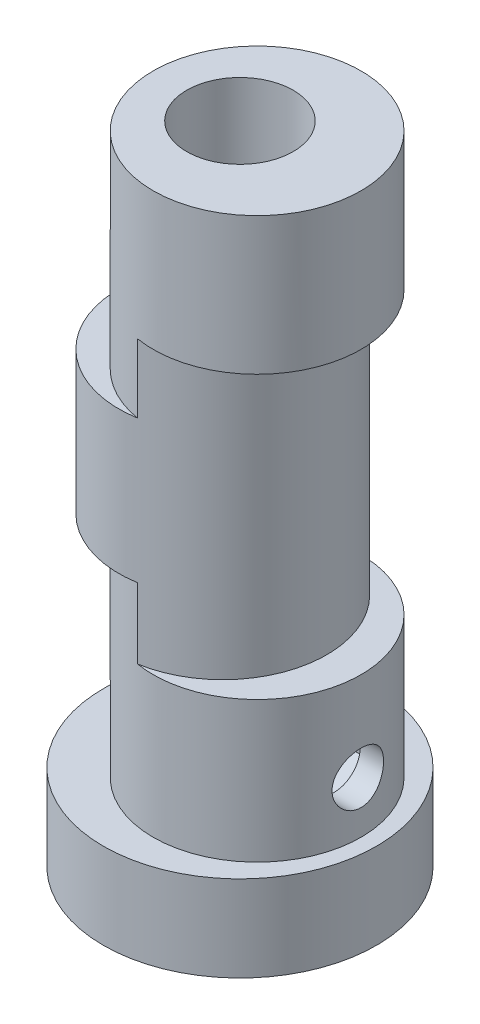
SolidWorks part; units mm, degrees
ref_plane "Front Plane" through (0, 0, 0) normal (0, 0, 1) x (1, 0, 0)
ref_plane "Top Plane" through (0, 0, 0) normal (0, 1, 0) x (1, 0, 0)
ref_plane "Right Plane" through (0, 0, 0) normal (1, 0, 0) x (0, 0, -1)
sketch "Sketch1" plane through (0, 0, 0) normal (0, 1, 0) x (1, 0, 0)
  circle A0 centre (0, 0) radius 7.95
  dimension "D1" = 15.9
extrude "Boss-Extrude1" add sketch "Sketch1" along normal blind 5
sketch "Sketch2" plane through (0, 5, 0) normal (0, 1, 0) x (1, 0, 0)
  line L0 (0, 0) -> (1, 0) construction
  circle A0 centre (1, 0) radius 6.05
  dimension "D2" = 12.1
  dimension "D1" = 1
extrude "Boss-Extrude2" add sketch "Sketch2" along normal blind 8.2
sketch "Sketch3" plane through (0, 13.2, 0) normal (0, 1, 0) x (1, 0, 0)
  line L0 (0, 0) -> (-1, 0) construction
  circle A0 centre (0, 0) radius 7.95 construction
  circle A1 centre (0, 0) radius 7.95 construction
  circle A2 centre (-1, 0) radius 6.05
  dimension "D2" = 12.1
  dimension "D1" = 1
extrude "Boss-Extrude3" add sketch "Sketch3" along normal blind 16.4
sketch "Sketch4" plane through (0, 13.2, 0) normal (0, -1, 0) x (1, 0, 0)
  arc A2 (0, 5.9668) -> (0, -5.9668) centre (-1, 0) ccw
  arc A3 (0, 5.9668) -> (0, -5.9668) centre (1, 0) ccw
  arc A4 (0, 5.9668) -> (0, -5.9668) centre (-1, 0) ccw
  arc A5 (0, 5.9668) -> (0, -5.9668) centre (1, 0) ccw
  dimension "D1" = 0
extrude "Cut-Extrude1" cut sketch "Sketch4" against normal blind 4.1
sketch "Sketch5" plane through (0, 29.6, 0) normal (0, 1, 0) x (1, 0, 0)
  line L0 (0, 0) -> (1, 0)
  circle A0 centre (1, 0) radius 6.05
  dimension "D2" = 12.1
  dimension "D1" = 1
extrude "Boss-Extrude4" add sketch "Sketch5" along normal blind 8
sketch "Sketch6" plane through (0, 29.6, 0) normal (0, 1, 0) x (1, 0, 0)
  arc A2 (0, 5.9668) -> (0, -5.9668) centre (1, 0) ccw
  arc A3 (0, 5.9668) -> (0, -5.9668) centre (-1, 0) ccw
  arc A4 (0, 5.9668) -> (0, -5.9668) centre (1, 0) ccw
  arc A5 (0, 5.9668) -> (0, -5.9668) centre (-1, 0) ccw
  dimension "D1" = 0
extrude "Cut-Extrude2" cut sketch "Sketch6" against normal blind 4
sketch "Sketch7" plane through (0, 0, 0) normal (0, -1, 0) x (1, 0, 0)
  circle A0 centre (0, 0) radius 3.1
  dimension "D1" = 6.2
extrude "Cut-Extrude3" cut sketch "Sketch7" against normal through all
sketch "Sketch8" plane through (0, 0, 0) normal (1, 0, 0) x (0, 0, -1)
  circle A0 centre (0, 8) radius 1.5
  dimension "D1" = 3
  dimension "D2" = 8
extrude "Cut-Extrude4" cut sketch "Sketch8" along normal through all
sketch "Sketch9" plane through (0, 0, 0) normal (1, 0, 0) x (0, 0, -1)
  line L1 (0, 11.1754) -> (-2.75, 9.5877)
  line L2 (-2.75, 9.5877) -> (-2.75, 6.4123)
  line L3 (-2.75, 6.4123) -> (0, 4.8246)
  line L4 (0, 4.8246) -> (2.75, 6.4123)
  line L5 (2.75, 6.4123) -> (2.75, 9.5877)
  line L6 (2.75, 9.5877) -> (0, 11.1754)
  circle A0 centre (0, 8) radius 1.5 construction
  circle A1 centre (0, 8) radius 1.5
  circle A2 centre (0, 8) radius 2.75 construction
  dimension "D1" = 5.5
extrude "Cut-Extrude5" cut sketch "Sketch9" along normal blind 5.5
